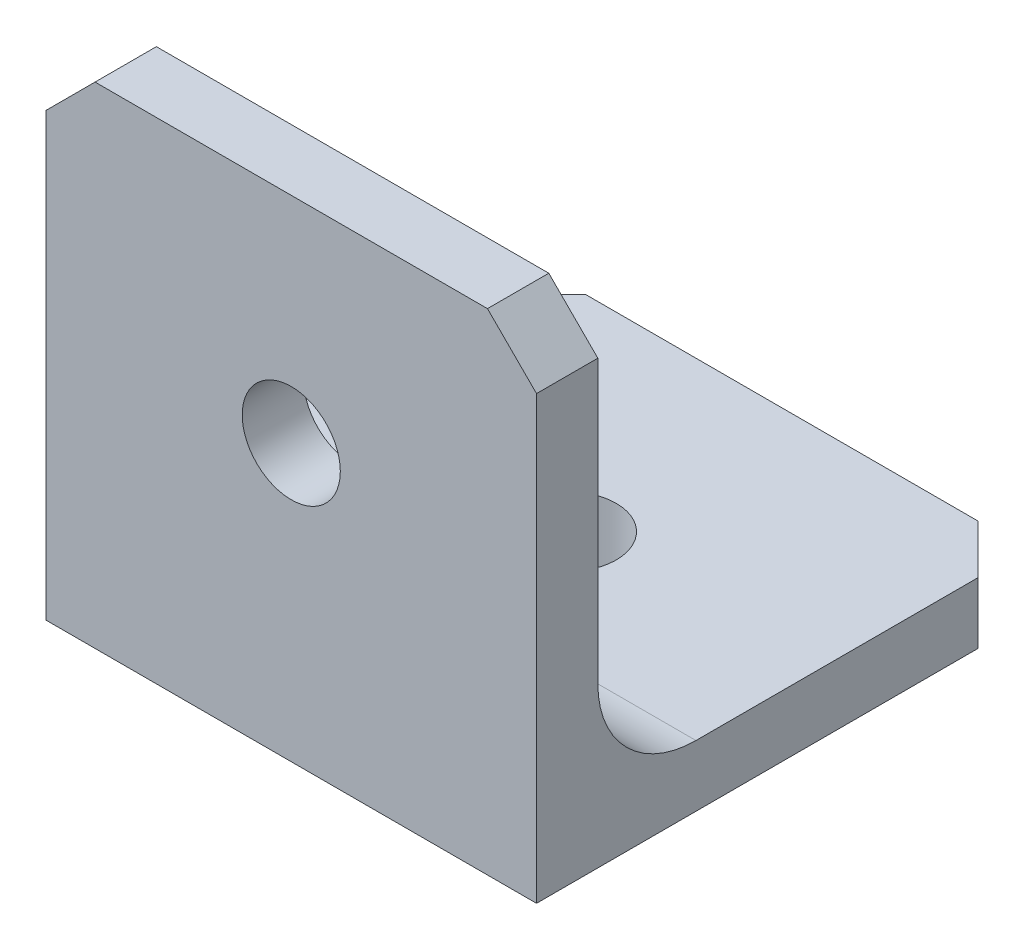
SolidWorks part; units mm, degrees
ref_plane "Front Plane" through (0, 0, 0) normal (0, 0, 1) x (1, 0, 0)
ref_plane "Top Plane" through (0, 0, 0) normal (0, 1, 0) x (1, 0, 0)
ref_plane "Right Plane" through (0, 0, 0) normal (1, 0, 0) x (0, 0, -1)
sketch "Sketch1" plane through (0, 0, 0) normal (1, 0, 0) x (0, 0, -1)
  line L0 (0, 0) -> (0, 25.4)
  line L1 (0, 25.4) -> (3.175, 25.4)
  line L2 (3.175, 25.4) -> (3.175, 3.175)
  line L3 (3.175, 3.175) -> (25.4, 3.175)
  line L4 (25.4, 3.175) -> (25.4, 0)
  line L5 (25.4, 0) -> (0, 0)
  dimension "1" = 25.4
  dimension "D2" = 3.175
extrude "Boss-Extrude1" add sketch "Sketch1" along normal blind 25.4
sketch "Sketch2" plane through (0, 0, 0) normal (0, 0, 1) x (1, 0, 0)
  line L0 (0, 25.4) -> (0, 0) construction
  line L2 (25.4, 25.4) -> (0, 25.4) construction
  circle A0 centre (12.7, 14.2875) radius 2.54
  dimension "D1" = 5.08
  dimension "D2" = 12.7
  dimension "D3" = 11.1125
extrude "Cut-Extrude1" cut sketch "Sketch2" against normal through all
sketch "Sketch3" plane through (0, 0, 0) normal (0, -1, 0) x (1, 0, 0)
  line L0 (25.4, -25.4) -> (0, -25.4) construction
  line L2 (25.4, 0) -> (25.4, -25.4) construction
  circle A0 centre (12.7, -14.2875) radius 2.54
  dimension "D1" = 5.08
  dimension "D2" = 11.1125
  dimension "D4" = 12.7
extrude "Cut-Extrude2" cut sketch "Sketch3" against normal through all
fillet "Fillet1" radius 5.08 1 edges at (12.7, 3.175, -3.175)
chamfer "Chamfer1" distance 2.54 angle 45 4 edges at (0, 1.5875, -25.4) (25.4, 1.5875, -25.4) (25.4, 25.4, -1.5875) (0, 25.4, -1.5875)
